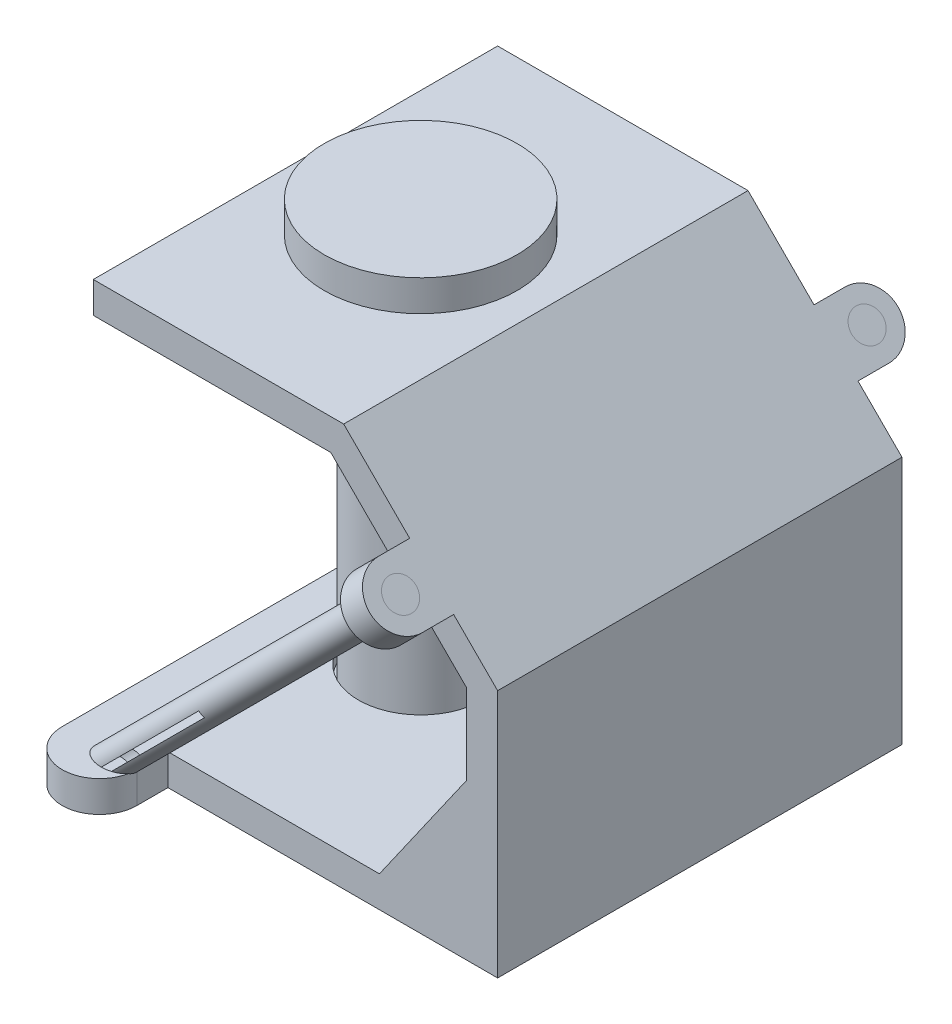
SolidWorks part; units mm, degrees
material "Chrome Stainless Steel"
ref_plane "Front Plane" through (0, 0, 0) normal (0, 0, 1) x (1, 0, 0)
ref_plane "Top Plane" through (0, 0, 0) normal (0, 1, 0) x (1, 0, 0)
ref_plane "Right Plane" through (0, 0, 0) normal (1, 0, 0) x (0, 0, -1)
sketch "Sketch1" plane through (0, 0, 0) normal (0, 0, 1) x (1, 0, 0)
  line L0 (0, 0) -> (65, 0)
  line L1 (65, 0) -> (65, 40)
  line L2 (65, 40) -> (40.2513, 64.7487)
  line L3 (40.2513, 64.7487) -> (0, 64.7487)
  line L4 (0, 64.7487) -> (0, 59.7487)
  line L5 (0, 59.7487) -> (38.1802, 59.7487)
  line L6 (38.1802, 59.7487) -> (60, 37.9289)
  line L7 (60, 37.9289) -> (60, 5)
  line L8 (60, 5) -> (0, 5)
  line L9 (0, 5) -> (0, 0)
  dimension "D1" = 65
  dimension "D2" = 40
  dimension "D3" = 35
  dimension "D4" = 135
  dimension "D5" = 5
  dimension "D6" = 5
  dimension "D7" = 5
  dimension "D8" = 5
extrude "Boss-Extrude1" add sketch "Sketch1" against normal mid plane 65
sketch "Sketch2" plane through (0, 0, 32.5) normal (0, 0, 1) x (1, 0, 0)
  line L0 (60, 25) -> (45.9958, 5)
  line L1 (60, 37.9289) -> (60, 5) construction
  line L2 (60, 5) -> (0, 5) construction
  dimension "D1" = 20
  dimension "D2" = 55
rib "Rib1" sketch "Sketch2" sketch "Sketch2" thickness 5 extrusion direction parallel to sketch draft on no parameters "D1"=5
mirror "Mirror1" about plane through (0, 0, 0) normal (0, 0, 1) of "Rib1"
sketch "Sketch3" plane through (52.5, 52.5, 0) normal (0.7071, 0.7071, 0) x (0, 0, -1)
  line L0 (-32.5, -7.6777) -> (-37.5, -7.6777)
  line L1 (-32.5, -17.6777) -> (-32.5, 17.3223) construction
  line L2 (-32.5, 2.3223) -> (-37.5, 2.3223)
  line L3 (32.5, -17.6777) -> (-32.5, -17.6777) construction
  line L4 (-32.5, 2.3223) -> (-32.5, -7.6777)
  arc A0 (-37.5, 2.3223) -> (-37.5, -7.6777) centre (-37.5, -2.6777) ccw
  dimension "D1" = 5
  dimension "D2" = 10
  dimension "D3" = 5
extrude "Boss-Extrude2" add sketch "Sketch3" against normal up to surface (5 mm away) up to face at (49.0901, 48.8388, 0)
mirror "Mirror2" about plane through (0, 0, 0) normal (0, 0, 1) of "Boss-Extrude2"
sketch "Sketch4" plane through (0, 5, 0) normal (0, 1, 0) x (1, 0, 0)
  line L0 (0, -32.5) -> (0, -37.5)
  line L1 (12, -32.5) -> (12, -37.5)
  line L2 (45.9958, -32.5) -> (0, -32.5) construction
  line L3 (0, -32.5) -> (12, -32.5)
  arc A0 (0, -37.5) -> (12, -37.5) centre (6, -37.5) ccw
  dimension "D1" = 6
  dimension "D2" = 5
extrude "Boss-Extrude3" add sketch "Sketch4" against normal up to surface (5 mm away) up to face at (32.5, 0, 0)
mirror "Mirror3" about plane through (0, 0, 0) normal (0, 0, 1) of "Boss-Extrude3"
sketch "Sketch5" plane through (52.5, 52.5, 0) normal (0.7071, 0.7071, 0) x (0, 0, -1)
  circle A0 centre (-37.5, -2.6777) radius 2.5
  dimension "D1" = 5
extrude "Cut-Extrude1" cut sketch "Sketch5" against normal offset from surface (69.8259 mm away) 3
mirror "Mirror4" about plane through (0, 0, 0) normal (0, 0, 1) of "Cut-Extrude1"
sketch "Sketch6" plane through (52.5, 52.5, 0) normal (0.7071, 0.7071, 0) x (0, 0, -1)
  circle A1 centre (-37.5, -2.6777) radius 2.5
  circle A2 centre (-37.5, -2.6777) radius 2.5 construction
extrude "Boss-Extrude4" add sketch "Sketch6" against normal up to surface (69.8259 mm away) separate body
mirror "Mirror7" about plane through (0, 0, 0) normal (0, 0, 1) of bodies 109
sketch "Sketch7" plane through (0, 64.7487, 0) normal (0, 1, 0) x (1, 0, 0)
  line L0 (20.1256, 10) -> (20.1256, 32.5) construction
  line L1 (40.2513, 32.5) -> (0, 32.5) construction
  line L2 (20.1256, -10) -> (20.1256, -32.5) construction
  line L3 (40.2513, -32.5) -> (0, -32.5) construction
  line L4 (0, 0) -> (10.1256, 0) construction
  line L5 (40.2513, 0) -> (30.1256, 0) construction
  line L6 (40.2513, 32.5) -> (40.2513, -32.5) construction
  circle A0 centre (20.1256, 0) radius 10
  dimension "D1" = 20
extrude "Cut-Extrude2" cut sketch "Sketch7" against normal offset from surface (61.7487 mm away) 3 up to face at (22.25, 0, 0)
sketch "Sketch8" plane through (0, 64.7487, 0) normal (0, 1, 0) x (1, 0, 0)
  circle A0 centre (20.1256, 0) radius 9.5
  circle A1 centre (20.1256, 0) radius 10 construction
  dimension "D1" = 19
extrude "Boss-Extrude5" add sketch "Sketch8" against normal up to surface (61.7487 mm away) separate body up to face at (20.1256, 3, -10)
sketch "Sketch9" plane through (0, 64.7487, 0) normal (0, 1, 0) x (1, 0, 0)
  circle A0 centre (20.1256, 0) radius 15.5
  circle A1 centre (20.1256, 0) radius 9.5 construction
  dimension "D1" = 31
extrude "Boss-Extrude6" add sketch "Sketch9" along normal blind 5 separate body
combine bodies "Combine1" operation type add bodies to combine 112 113
other "Save Bodies1"
ref_plane "Plane2" through (0, 0, -40) normal (0, 0, -1) x (-1, 0, 0)
sketch "Sketch12" plane through (0, 0, -40) normal (0, 0, -1) x (-1, 0, 0)
  line L0 (-24.4645, 20.6777) -> (-6.7868, 3)
  line L1 (-12.2611, 32.8811) -> (-36.6679, 8.4743) construction
  line L2 (-3.2513, 3) -> (-10.3223, 3) construction
  line L3 (-38.1802, 59.7487) -> (-47.3223, 50.6066) construction
  point P6 (-22.7769, 24.7132)
  point P7 (0, 0)
  point P8 (-25.1107, 18.5865)
  point P9 (-21.2598, 22.4968)
  point P10 (-25.3924, 19.109)
  point P11 (-24.5641, 19.873)
  point P12 (-36.0557, 7.112)
  dimension "D1" = 25
extrude "Cut-Extrude-Thin1" cut sketch "Sketch12" against normal through all and the other way through all thin
equation "\"B\"= 55"
equation "\"D2@Sketch2\"=\"B\""
equation "\"A\" = 5"
equation "\"D1@Sketch3\"=\"A\""
equation "\"D1@Sketch5\"=\"A\""
equation "\"C\"= \"A\" * 2 + 10"
equation "\"D1@Sketch7\"=\"C\""
equation "\"D1@Sketch8\"=\"C\"-1"
